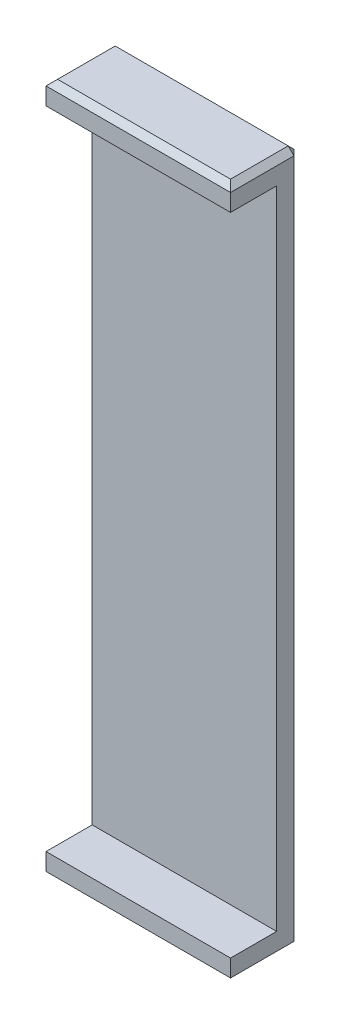
SolidWorks part; units mm, degrees
ref_plane "前基準面" through (0, 0, 0) normal (0, 0, 1) x (1, 0, 0)
ref_plane "上基準面" through (0, 0, 0) normal (0, 1, 0) x (1, 0, 0)
ref_plane "右基準面" through (0, 0, 0) normal (1, 0, 0) x (0, 0, -1)
sketch "草圖1" plane through (0, 0, 0) normal (0, 0, 1) x (1, 0, 0)
  line L1 (38.4358, 159.2858) -> (118.4358, 159.2858)
  line L2 (38.4358, 159.2858) -> (38.4358, -140.7142)
  line L3 (38.4358, -140.7142) -> (118.4358, -140.7142)
  line L4 (118.4358, 159.2858) -> (118.4358, -140.7142)
  dimension "D1" = 80
  dimension "D2" = 300
extrude "填料-伸長1" add sketch "草圖1" against normal blind 10
sketch "草圖2" plane through (0, 0, 0) normal (0, 0, 1) x (1, 0, 0)
  line L0 (118.4358, -140.7142) -> (118.4358, 159.2858) construction
  line L1 (38.4358, -140.7142) -> (118.4358, -140.7142)
  line L2 (38.4358, -140.7142) -> (38.4358, -130.7142)
  line L3 (38.4358, -130.7142) -> (118.4358, -130.7142)
  line L4 (118.4358, -140.7142) -> (118.4358, -130.7142)
  line L6 (38.4358, 159.2858) -> (118.4358, 159.2858)
  line L7 (38.4358, 159.2858) -> (38.4358, 149.2858)
  line L8 (38.4358, 149.2858) -> (118.4358, 149.2858)
  line L9 (118.4358, 159.2858) -> (118.4358, 149.2858)
  dimension "D1" = 10
  dimension "D2" = 10
extrude "填料-伸長2" add sketch "草圖2" along normal blind 20
chamfer "導角1" distance 2.5 angle 45 10 edges at (118.4358, 159.2858, 5) (78.4358, 159.2858, 20) (38.4358, 159.2858, 5) (118.4358, 9.2858, -10) (78.4358, 159.2858, -10) (38.4358, 9.2858, -10) (78.4358, -140.7142, -10) (38.4358, -140.7142, 5) (78.4358, -140.7142, 20) (118.4358, -140.7142, 5)
